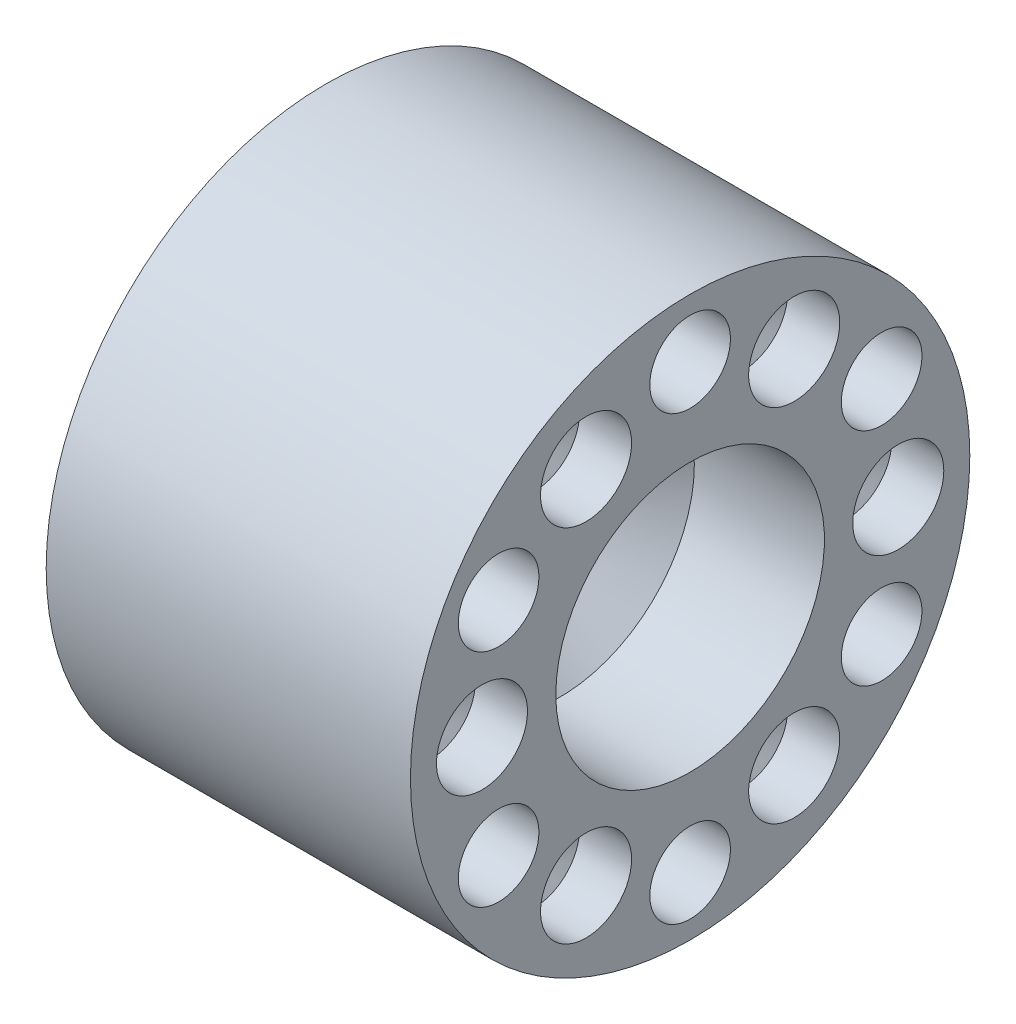
SolidWorks part; units mm, degrees
material "2018 Alloy"
ref_plane "Front Plane" through (0, 0, 0) normal (0, 0, 1) x (1, 0, 0)
ref_plane "Top Plane" through (0, 0, 0) normal (0, 1, 0) x (1, 0, 0)
ref_plane "Right Plane" through (0, 0, 0) normal (1, 0, 0) x (0, 0, -1)
sketch "Sketch1" plane through (0, 0, 0) normal (0, 0, 1) x (1, 0, 0)
  line L2 (4, 18.5) -> (0, 15)
  line L4 (0, 8.3175) -> (0, 0) construction
  line L5 (32, 0) -> (32, 10.325) construction
  line L7 (0, 0) -> (32, 0) construction
  line L13 (32, 10.325) -> (22, 10.325)
  line L14 (22, 10.325) -> (18.175, 6.5)
  line L15 (18.175, 6.5) -> (0, 8.3175)
  line L16 (4, 18.5) -> (4, 21.5)
  line L17 (4, 21.5) -> (32, 21.5)
  line L18 (0, 15) -> (0, 8.3175)
  line L26 (32, 21.5) -> (32, 10.325)
  line L27 (18.175, 6.5) -> (8.175, 6.5) construction
  line L28 (8.175, 6.5) -> (8.175, 7.5) construction
  dimension "D4" = 32
  dimension "D5" = 28
  dimension "D6" = 10
  dimension "D8" = 20.65
  dimension "D9" = 45
  dimension "D10" = 13
  dimension "D13" = 4
  dimension "D14" = 37
  dimension "D15" = 30
  dimension "D16" = 43
  dimension "D17" = 48.814
  dimension "D19" = 18.175
  dimension "D20" = 10
  dimension "D27" = 1
  dimension "D28" = 5.711
  dimension "D29" = 16.635
  dimension "D31" = 3.825
revolve "Revolve1" add sketch "Sketch1" angle 360 about L7
sketch "Sketch11" plane through (32, 0, 0) normal (1, 0, 0) x (0, 0, -1)
  line L0 (0, 0) -> (0, -17) construction
  circle A0 centre (0, 0) radius 17 construction
  circle A1 centre (0, -17) radius 3.1
  circle A2 centre (-14.7224, -8.5) radius 3.1
  circle A3 centre (-14.7224, 8.5) radius 3.1
  circle A4 centre (0, 17) radius 3.1
  circle A5 centre (14.7224, 8.5) radius 3.1
  circle A6 centre (14.7224, -8.5) radius 3.1
  dimension "D1" = 34
  dimension "D2" = 6.2
extrude "Extrude1" cut sketch "Sketch11" against normal blind 12
sketch "Sketch12" plane through (20, 0, 0) normal (1, 0, 0) x (0, 0, -1)
  circle A0 centre (0, -17) radius 3
  circle A1 centre (-14.7224, -8.5) radius 3
  circle A2 centre (-14.7224, 8.5) radius 3
  circle A3 centre (0, 17) radius 3
  circle A4 centre (14.7224, 8.5) radius 3
  circle A5 centre (14.7224, -8.5) radius 3
  dimension "D1" = 6
hole_wizard "M6 Tapped Hole1" positions "3DSketch1" profile "Sketch13" tap size "M6" standard "DIN"
sketch3d "3DSketch1"
  point P0 (20, -17, 0)
  point P3 (20, -8.5, 14.7224)
  point P6 (20, 8.5, 14.7224)
  point P9 (20, 17, 0)
  point P12 (20, 8.5, -14.7224)
  point P15 (20, -8.5, -14.7224)
sketch "Sketch13" plane through (20, -17, 0) normal (0, 1, 0) x (0, 0, -1)
  line L0 (0, 0) -> (0, 36.5022)
  line L1 (0, 36.5022) -> (2.5, 35)
  line L2 (2.5, 35) -> (2.5, 0)
  line L5 (2.5, 0) -> (0, 0)
  line L10 (0, 36.5022) -> (-2.5, 35) construction
  line L11 (0, -6.35) -> (0, 107.95) construction
  dimension "Tap Drill Dia." = 5
  dimension "Tap Drill Depth" = 35
  dimension "Drill Angle" = 118
cosmetic thread "Hole Thread3"
cosmetic thread "Hole Thread4"
cosmetic thread "Hole Thread5"
cosmetic thread "Hole Thread6"
cosmetic thread "Hole Thread7"
cosmetic thread "Hole Thread8"
sketch "Sketch14" plane through (32, 0, 0) normal (1, 0, 0) x (0, 0, -1)
  line L0 (0, -16) -> (0, 0) construction
  line L1 (0, 0) -> (8, -13.8564) construction
  circle A0 centre (0, 0) radius 16 construction
  circle A1 centre (8, -13.8564) radius 3.5
  circle A2 centre (-8, -13.8564) radius 3.5
  circle A3 centre (-16, 0) radius 3.5
  circle A4 centre (-8, 13.8564) radius 3.5
  circle A5 centre (8, 13.8564) radius 3.5
  circle A6 centre (16, 0) radius 3.5
  dimension "D1" = 32
  dimension "D3" = 7
  dimension "D2" = 30
hole_wizard "Ø7.0 (7) Diameter Hole1" positions "3DSketch2" profile "Sketch15" hole size "Ø7.0" standard "DIN"
sketch3d "3DSketch2"
  point P0 (32, -13.8564, -8)
  point P3 (32, -13.8564, 8)
  point P6 (32, 0, 16)
  point P9 (32, 13.8564, 8)
  point P12 (32, 13.8564, -8)
  point P15 (32, 0, -16)
sketch "Sketch15" plane through (32, -13.8564, -8) normal (0, 1, 0) x (0, 0, -1)
  line L0 (0, 0) -> (0, 6.103)
  line L1 (0, 6.103) -> (3.5, 4)
  line L2 (3.5, 4) -> (3.5, 0)
  line L5 (3.5, 0) -> (0, 0)
  line L10 (0, 6.103) -> (-3.5, 4) construction
  line L11 (0, -6.35) -> (0, 107.95) construction
  dimension "Hole Dia." = 7
  dimension "Hole Depth" = 4
  dimension "Drill Angle" = 118
sketch "Sketch17" plane through (0, 0, 0) normal (0, 0, 1) x (1, 0, 0)
  line L0 (0, 0) -> (0, 33.2506)
sketch "Sketch18" plane through (0, 0, 0) normal (0, 0, 1) x (1, 0, 0)
  line L0 (21.0706, 5.306) -> (-1.0846, 7.5215)
  line L1 (-1.0846, 7.5215) -> (-0.7861, 10.5066)
  line L2 (-0.7861, 10.5066) -> (21.3691, 8.2911)
  line L3 (21.3691, 8.2911) -> (21.0706, 5.306)
  line L4 (18.175, 6.5) -> (0, 8.3175) construction
  dimension "D1" = 2.1
  dimension "D2" = 3
  dimension "D3" = 1
  dimension "D4" = 3
extrude "Extrude3" cut sketch "Sketch18" against normal mid plane 2
